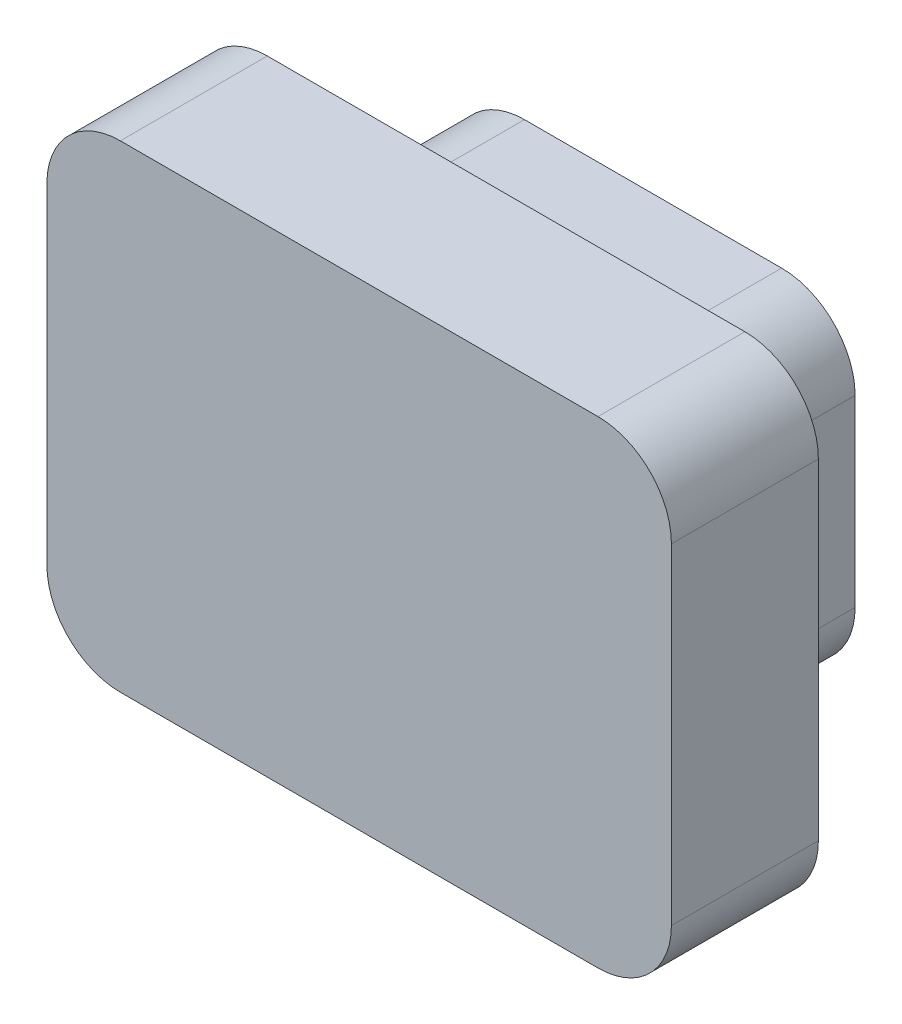
SolidWorks part; units mm, degrees
ref_plane "Спереди" through (0, 0, 0) normal (0, 0, 1) x (1, 0, 0)
ref_plane "Сверху" through (0, 0, 0) normal (0, 1, 0) x (1, 0, 0)
ref_plane "Справа" through (0, 0, 0) normal (1, 0, 0) x (0, 0, -1)
sketch "Эскиз1" plane through (0, 0, 0) normal (0, 0, 1) x (1, 0, 0)
  line L1 (-1.75, -2.25) -> (1.75, -2.25)
  line L2 (-2.75, -1.25) -> (-2.75, 1.25)
  line L3 (-1.75, 2.25) -> (1.75, 2.25)
  line L4 (2.75, -1.25) -> (2.75, 1.25)
  line L5 (-2.75, -2.25) -> (2.75, 2.25) construction
  line L6 (-2.75, 2.25) -> (2.75, -2.25) construction
  arc A1 (1.75, -2.25) -> (2.75, -1.25) centre (1.75, -1.25) ccw
  arc A2 (2.75, 1.25) -> (1.75, 2.25) centre (1.75, 1.25) ccw
  arc A3 (-1.75, -2.25) -> (-2.75, -1.25) centre (-1.75, -1.25) cw
  arc A4 (-2.75, 1.25) -> (-1.75, 2.25) centre (-1.75, 1.25) cw
  point P0 (0, 0)
  dimension "D1" = 5.5
  dimension "D3" = 1
  dimension "D2" = 4.5
extrude "Бобышка-Вытянуть1" add sketch "Эскиз1" along normal blind 2
sketch "Эскиз2" plane through (0, 0, 2) normal (0, 0, 1) x (1, 0, 0)
  line L1 (-3.25, -3.25) -> (3.25, -3.25)
  line L2 (-4.25, -2.25) -> (-4.25, 2.25)
  line L3 (-3.25, 3.25) -> (3.25, 3.25)
  line L4 (4.25, -2.25) -> (4.25, 2.25)
  line L5 (-4.25, -3.25) -> (4.25, 3.25) construction
  line L6 (-4.25, 3.25) -> (4.25, -3.25) construction
  arc A0 (-4.25, -2.25) -> (-3.25, -3.25) centre (-3.25, -2.25) ccw
  arc A1 (3.25, -3.25) -> (4.25, -2.25) centre (3.25, -2.25) ccw
  arc A2 (4.25, 2.25) -> (3.25, 3.25) centre (3.25, 2.25) ccw
  arc A3 (-4.25, 2.25) -> (-3.25, 3.25) centre (-3.25, 2.25) cw
  point P0 (0, 0)
  dimension "D3" = 1
  dimension "D1" = 8.5
  dimension "D2" = 6.5
extrude "Бобышка-Вытянуть2" add sketch "Эскиз2" along normal blind 2
